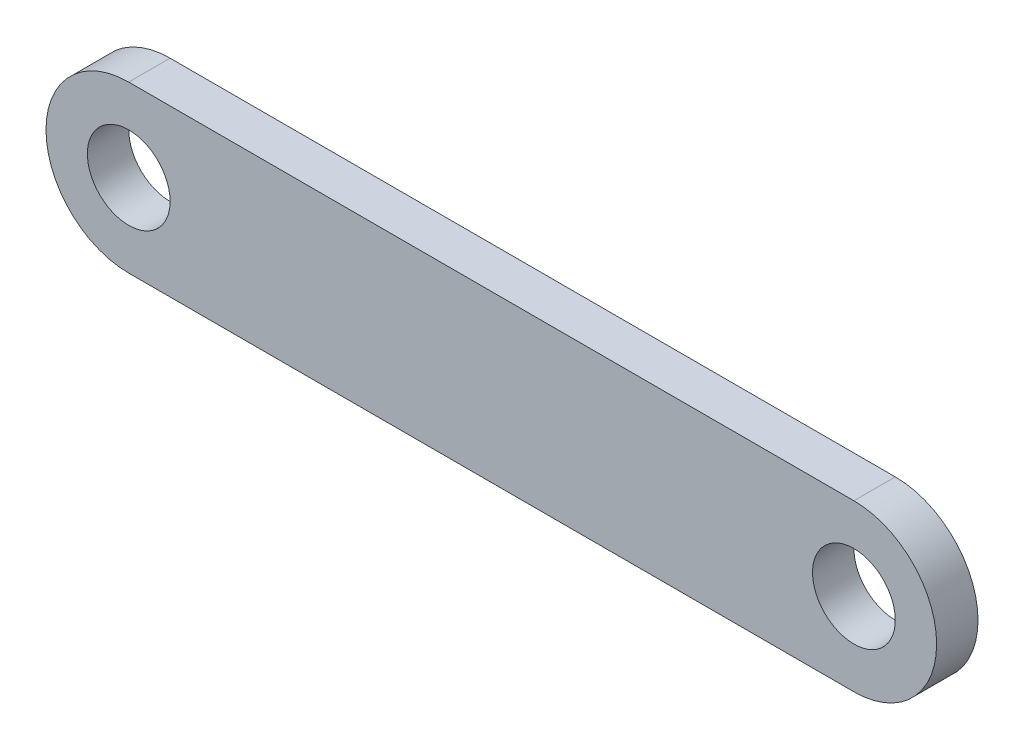
SolidWorks part; units mm, degrees
ref_plane "Спереди" through (0, 0, 0) normal (0, 0, 1) x (1, 0, 0)
ref_plane "Сверху" through (0, 0, 0) normal (0, 1, 0) x (1, 0, 0)
ref_plane "Справа" through (0, 0, 0) normal (1, 0, 0) x (0, 0, -1)
sketch "Sketch1" plane through (0, 0, 0) normal (0, 0, 1) x (1, 0, 0)
  line L0 (0, 0) -> (17.53, 0)
  line L1 (0, 2) -> (17.53, 2)
  line L2 (0, -2) -> (17.53, -2)
  circle A0 centre (0, 0) radius 1
  circle A1 centre (17.53, 0) radius 1
  circle A2 centre (0, 0) radius 2
  circle A3 centre (17.53, 0) radius 2
  dimension "D1" = 17.53
extrude "Extrude1" add sketch "Sketch1" against normal blind 1
